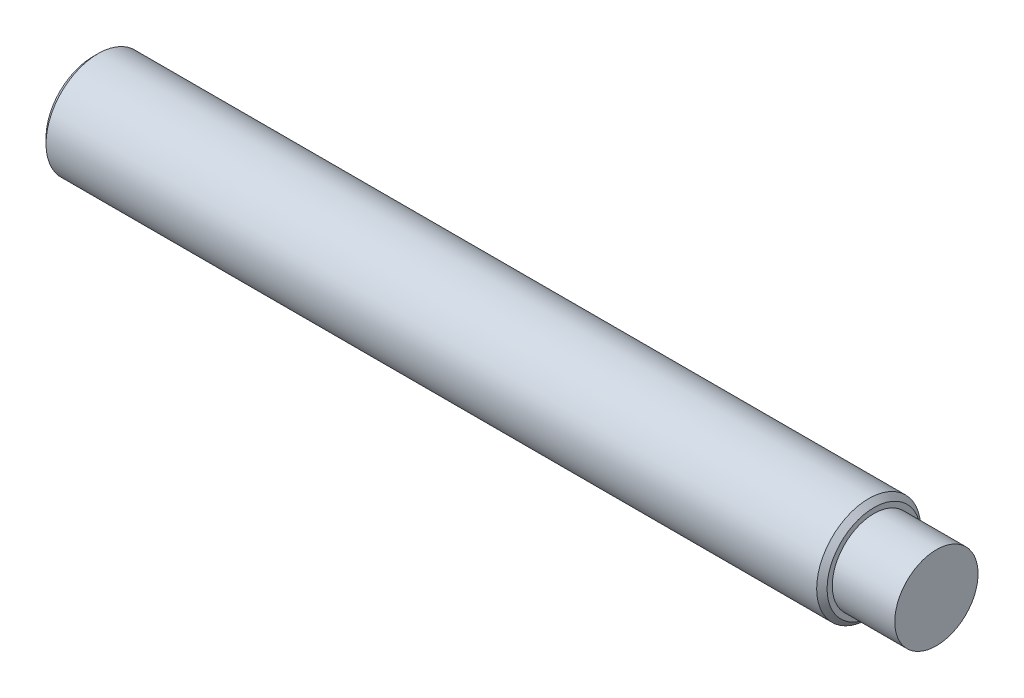
SolidWorks part; units mm, degrees
ref_plane "Front Plane" through (0, 0, 0) normal (0, 0, 1) x (1, 0, 0)
ref_plane "Top Plane" through (0, 0, 0) normal (0, 1, 0) x (1, 0, 0)
ref_plane "Right Plane" through (0, 0, 0) normal (1, 0, 0) x (0, 0, -1)
sketch "Sketch1" plane through (0, 0, 0) normal (0, 0, 1) x (1, 0, 0)
  line L0 (0, 0) -> (0, 5)
  line L1 (0, 5) -> (75, 5)
  line L2 (75, 5) -> (75, 4)
  line L3 (75, 4) -> (81, 4)
  line L4 (81, 4) -> (81, 0)
  line L5 (81, 0) -> (0, 0)
  line L6 (-21.6251, 0) -> (57.019, 0) construction
  dimension "D1" = 75
  dimension "D2" = 6
  dimension "D3" = 10
  dimension "D4" = 8
revolve "Revolve1" add sketch "Sketch1" angle 360 about L6
chamfer "Chamfer1" distance 0.5 angle 45 2 edges at (75, 0, 5) (0, 0, 5)
sketch "Sketch6" plane through (0, 0, 0) normal (-1, 0, 0) x (0, 0, 1)
  circle A0 centre (0, 0) radius 2
  dimension "D1" = 4
extrude "Cut-Extrude1" cut sketch "Sketch6" against normal blind 10
